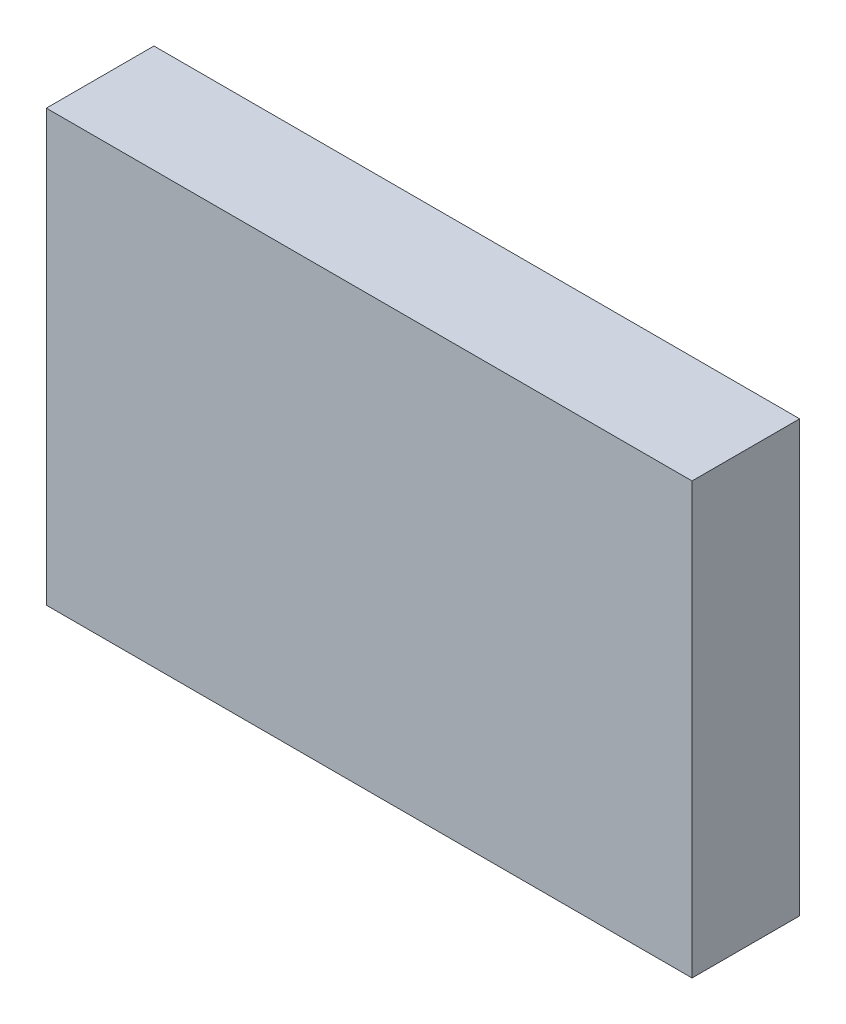
SolidWorks part; units mm, degrees
ref_plane "Přední rovina" through (0, 0, 0) normal (0, 0, 1) x (1, 0, 0)
ref_plane "Horní rovina" through (0, 0, 0) normal (0, 1, 0) x (1, 0, 0)
ref_plane "Pravá rovina" through (0, 0, 0) normal (1, 0, 0) x (0, 0, -1)
ref_plane "Plane2" through (0, 0, 50) normal (0, 0, 1) x (1, 0, 0)
sketch "Sketch3" plane through (0, 0, 50) normal (0, 0, 1) x (1, 0, 0)
  line L1 (15, -10) -> (-15, -10)
  line L2 (15, -10) -> (15, 10)
  line L3 (15, 10) -> (-15, 10)
  line L4 (-15, -10) -> (-15, 10)
  line L5 (15, -10) -> (-15, 10) construction
  line L6 (15, 10) -> (-15, -10) construction
  point P0 (0, 0)
  dimension "D1" = 30
  dimension "D2" = 20
extrude "Boss-Extrude1" add sketch "Sketch3" along normal blind 5
sketch "Sketch7" plane through (0, 10, 0) normal (0, 1, 0) x (1, 0, 0)
  line L0 (15, -55) -> (15, -50)
  line L1 (15, -55) -> (-15.5788, -55)
  line L2 (15, -50) -> (-15.5788, -50)
  line L3 (-15.5788, -55) -> (-15.5788, -50)
equation "\"SH\" = 3mm"
equation "\"OH\" = 5mm"
equation "\"D1@Boss-Extrude1\"=\"OH\""
